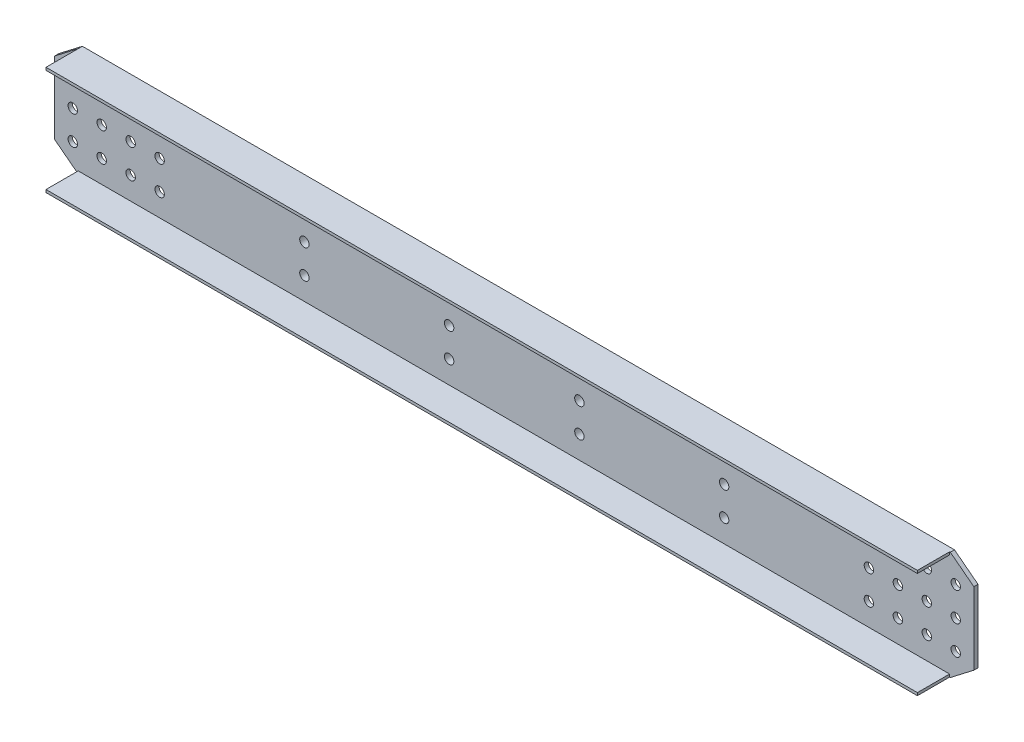
SolidWorks part; units mm, degrees
ref_plane "前视" through (0, 0, 0) normal (0, 0, 1) x (1, 0, 0)
ref_plane "上视" through (0, 0, 0) normal (0, 1, 0) x (1, 0, 0)
ref_plane "右视" through (0, 0, 0) normal (1, 0, 0) x (0, 0, -1)
sketch "草图1" plane through (0, 0, 0) normal (0, 0, 1) x (1, 0, 0)
  line L0 (0, -30.9807) -> (0, 402.9291) construction
  line L1 (-1205, 0) -> (1205, 0)
  line L2 (-1270, 50) -> (-1270, 250)
  line L3 (-1205, 300) -> (1205, 300)
  line L4 (-1270, 50) -> (-1205, 0)
  line L5 (-1270, 250) -> (-1205, 300)
  line L6 (-1329.5124, 150) -> (23.7415, 150) construction
  line L7 (-1307.9834, 230) -> (-31.6189, 230) construction
  line L8 (-1220, -101.4655) -> (-1220, 369.0978) construction
  line L9 (1270, 250) -> (1205, 300)
  line L10 (-1140, 369.0978) -> (-1140, -101.4655) construction
  line L11 (1270, 50) -> (1205, 0)
  line L12 (-1060, -101.4655) -> (-1060, 369.0978) construction
  line L13 (1270, 50) -> (1270, 250)
  line L14 (-980, 369.0978) -> (-980, -101.4655) construction
  circle A0 centre (-1220, 230) radius 13
  circle A1 centre (-1220, 150) radius 13
  circle A2 centre (-1140, 230) radius 13
  circle A3 centre (-1140, 150) radius 13
  circle A4 centre (-1060, 230) radius 13
  circle A5 centre (-1060, 150) radius 13
  circle A6 centre (-980, 150) radius 13
  circle A7 centre (-1060, 70) radius 13
  circle A8 centre (-1140, 70) radius 13
  circle A9 centre (-1220, 70) radius 13
  circle A10 centre (1220, 70) radius 13
  circle A11 centre (1140, 70) radius 13
  circle A12 centre (1060, 70) radius 13
  circle A13 centre (980, 150) radius 13
  circle A14 centre (1060, 150) radius 13
  circle A15 centre (1060, 230) radius 13
  circle A16 centre (1140, 150) radius 13
  circle A17 centre (1140, 230) radius 13
  circle A18 centre (1220, 150) radius 13
  circle A19 centre (1220, 230) radius 13
  circle A20 centre (-980, 70) radius 13
  circle A21 centre (-980, 230) radius 13
  circle A22 centre (980, 70) radius 13
  circle A23 centre (980, 230) radius 13
  point P8 (0, 300)
  point P65 (0, 0)
  dimension "D13" = 26
  dimension "D14" = 26
  dimension "D1" = 1205
  dimension "D2" = 300
  dimension "D3" = 65
  dimension "D4" = 65
  dimension "D5" = 50
  dimension "D6" = 50
  dimension "D7" = 70
  dimension "D8" = 80
  dimension "D9" = 50
  dimension "D10" = 80
  dimension "D11" = 80
  dimension "D12" = 80
  dimension "D15" = 70
  dimension "D16" = 70
extrude "基体-拉伸" add sketch "草图1" against normal blind 11.5
sketch "草图2" plane through (0, 0, 0) normal (0, 0, 1) x (1, 0, 0)
  line L0 (-1399.9508, 150) -> (-832.4876, 150) construction
  line L1 (-1205, 300) -> (1203.049, 300)
  line L2 (-1205, 300) -> (-1205, 292.5)
  line L3 (-1205, 292.5) -> (1203.049, 292.5)
  line L4 (1203.049, 300) -> (1203.049, 292.5)
  line L5 (-1205, 0) -> (1205, 0) construction
  line L6 (1203.049, 0) -> (1203.049, 7.5)
  line L7 (-1205, 7.5) -> (1203.049, 7.5)
  line L8 (-1205, 0) -> (-1205, 7.5)
  line L9 (-1205, 0) -> (1203.049, 0)
  dimension "D1" = 7.5
extrude "凸台-拉伸1" add sketch "草图2" along normal blind 89
sketch "草图3" plane through (0, 0, -11.5) normal (0, 0, -1) x (-1, 0, 0)
  line L0 (0, -46.5184) -> (0, 412.0245) construction
  line L1 (-180, 412.0245) -> (-180, -46.5184) construction
  line L2 (-580, 412.0245) -> (-580, -73.5011) construction
  line L3 (-1205, 300) -> (1205, 300) construction
  line L4 (-620, 270) -> (-540, 270)
  line L5 (-620, 270) -> (-620, 30)
  line L6 (-620, 30) -> (-540, 30)
  line L7 (-540, 270) -> (-540, 30)
  line L8 (-220, 270) -> (-140, 270)
  line L9 (-220, 270) -> (-220, 30)
  line L10 (-220, 30) -> (-140, 30)
  line L11 (-140, 270) -> (-140, 30)
  line L12 (140, 270) -> (140, 30)
  line L13 (220, 30) -> (140, 30)
  line L14 (220, 270) -> (220, 30)
  line L15 (220, 270) -> (140, 270)
  line L16 (540, 270) -> (540, 30)
  line L17 (620, 30) -> (540, 30)
  line L18 (620, 270) -> (620, 30)
  line L19 (620, 270) -> (540, 270)
  dimension "D1" = 180
  dimension "D2" = 400
  dimension "D3" = 240
  dimension "D4" = 30
  dimension "D5" = 80
  dimension "D6" = 80
extrude "凸台-拉伸2" add sketch "草图3" along normal blind 16
sketch "草图4" plane through (0, 0, 0) normal (0, 0, 1) x (1, 0, 0)
  line L0 (0, -259.4133) -> (0, 624.9194) construction
  line L1 (-180, -162.9649) -> (-180, 487.5033) construction
  line L2 (1203.049, 300) -> (-1205, 300) construction
  line L3 (-580, 487.5033) -> (-580, -162.9649) construction
  line L4 (-781.6864, 230) -> (-55.0372, 230) construction
  line L6 (-55.0372, 150) -> (-781.6864, 150) construction
  line L8 (-781.6864, 70) -> (-55.0372, 70) construction
  circle A0 centre (-580, 230) radius 13
  circle A1 centre (-580, 150) radius 13
  circle A2 centre (-180, 230) radius 13
  circle A3 centre (-180, 150) radius 13
  circle A4 centre (-180, 70) radius 13
  circle A5 centre (-580, 70) radius 13
  circle A6 centre (580, 70) radius 13
  circle A7 centre (180, 70) radius 13
  circle A8 centre (180, 150) radius 13
  circle A9 centre (180, 230) radius 13
  circle A10 centre (580, 150) radius 13
  circle A11 centre (580, 230) radius 13
  dimension "D6" = 26
  dimension "D1" = 180
  dimension "D2" = 400
  dimension "D3" = 70
  dimension "D4" = 80
  dimension "D5" = 80
extrude "切除-拉伸1" cut sketch "草图4" against normal through all
